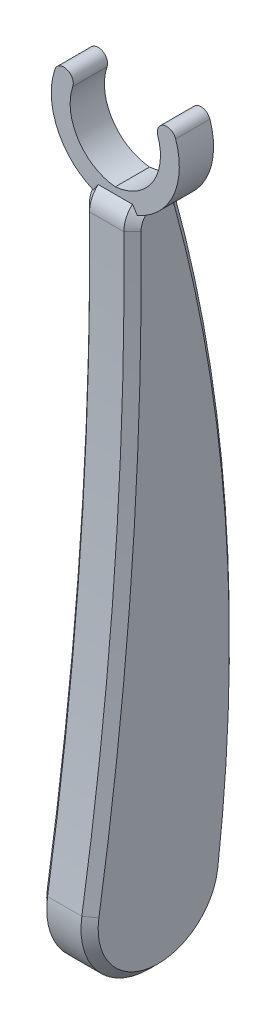
SolidWorks part; units mm, degrees
ref_plane "Front Plane" through (0, 0, 0) normal (1, 0, 0) x (0, 1, 0)
ref_plane "Top Plane" through (0, 0, 0) normal (0, 0, 1) x (0, 1, 0)
ref_plane "Right Plane" through (0, 0, 0) normal (0, 1, 0) x (-1, 0, 0)
sketch "Sketch1" plane through (0, 0, 0) normal (1, 0, 0) x (0, 1, 0)
  line L0 (-85, 0) -> (85, 0) construction
  arc A0 (-81.8718, 19.7538) -> (-87.4615, -19.8479) centre (-85, 0) ccw
  arc A1 (86.9844, -7.2327) -> (84.9221, 7.4996) centre (85, 0) ccw
  arc A2 (-81.8718, 19.7538) -> (84.9221, 7.4996) centre (74.5404, 1007.4457) ccw
  arc A3 (-87.4615, -19.8479) -> (86.9844, -7.2327) centre (-32.0772, 426.7308) ccw
  point P4 (0, 0)
  dimension "D2" = 15
  dimension "D3" = 40
  dimension "D4" = 450
  dimension "D5" = 1000
  dimension "D1" = 170
extrude "Boss-Extrude1" add sketch "Sketch1" along normal mid plane 15
chamfer "Chamfer1" distance 2.5 angle 45 6 edges at (-7.5, 0.3802, -22.0971) (-7.5, -104.8037, 2.7953) (-7.5, 1.2686, 10.1337) (7.5, 0.3802, -22.0971) (7.5, -104.8037, 2.7953) (7.5, 1.2686, 10.1337)
sketch "Sketch2" plane through (-7.5, 0, 0) normal (-1, 0, 0) x (0, -1, 0)
  circle A0 centre (85, 0) radius 5
extrude "Boss-Extrude2" add sketch "Sketch2" along normal blind 10
sketch "Sketch4" plane through (0, 0, 0) normal (0, 0, 1) x (0, 1, 0)
  line L0 (0, 0) -> (92.5, 0) construction
  line L1 (92.5, -5) -> (92.5, 5) construction
  line L2 (86.9844, -5) -> (86.9844, 5) construction
  arc A0 (86.9844, 0) -> (113.3861, -17.6027) centre (106.9401, 1.3301) ccw
  arc A1 (92.5, 0) -> (111.6139, -12.3973) centre (106.9401, 1.3301) ccw
  arc A2 (113.3861, -17.6027) -> (111.6139, -12.3973) centre (112.5, -15) ccw
  arc A3 (113.3861, 17.6027) -> (111.6139, 12.3973) centre (112.5, 15) cw
  arc A4 (92.5, 0) -> (111.6139, 12.3973) centre (106.9401, -1.3301) cw
  arc A5 (86.9844, 0) -> (113.3861, 17.6027) centre (106.9401, -1.3301) cw
  dimension "D1" = 20
  dimension "D2" = 15
  dimension "D3" = 20
extrude "Boss-Extrude3" add sketch "Sketch4" along normal mid plane 10
